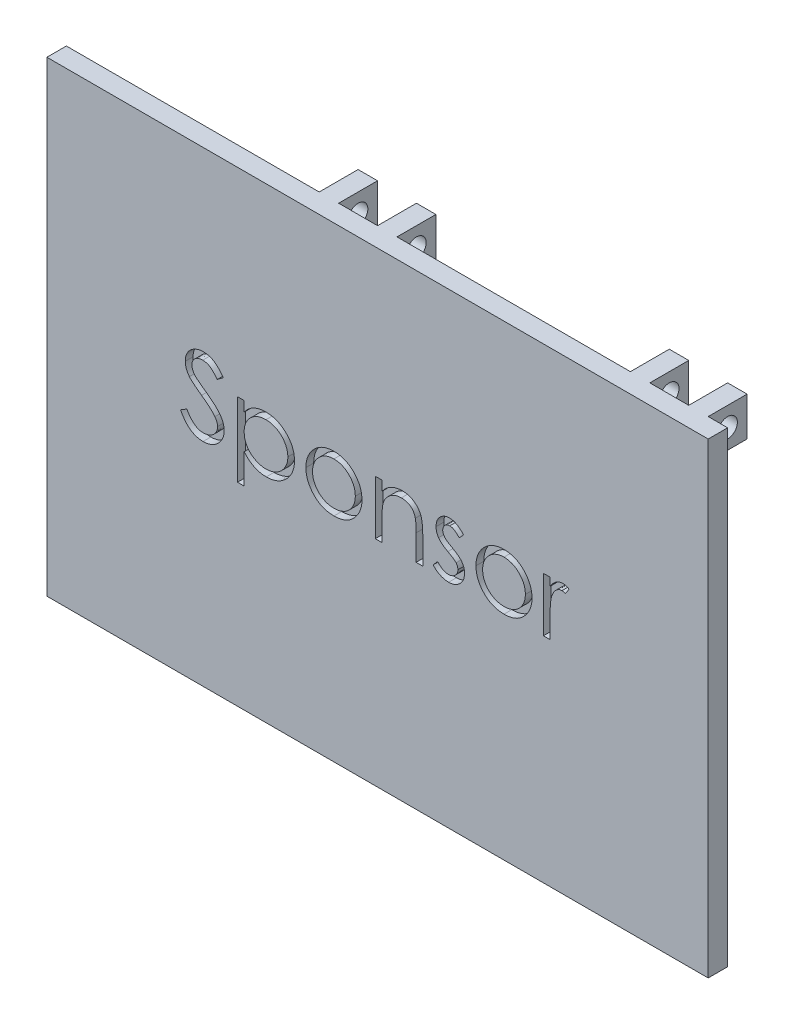
SolidWorks part; units mm, degrees
ref_plane "Plan de face" through (0, 0, 0) normal (0, 0, 1) x (1, 0, 0)
ref_plane "Plan de dessus" through (0, 0, 0) normal (0, 1, 0) x (1, 0, 0)
ref_plane "Plan de droite" through (0, 0, 0) normal (1, 0, 0) x (0, 0, -1)
sketch "Esquisse1" plane through (0, 0, 0) normal (0, 0, 1) x (1, 0, 0)
  line L1 (85, 60) -> (-85, 60)
  line L2 (85, 60) -> (85, -60)
  line L3 (85, -60) -> (-85, -60)
  line L4 (-85, 60) -> (-85, -60)
  line L5 (85, 60) -> (-85, -60) construction
  line L6 (85, -60) -> (-85, 60) construction
  point P0 (0, 0)
  dimension "D1" = 120
  dimension "D2" = 170
extrude "BASE" add sketch "Esquisse1" along normal blind 5
sketch "Esquisse2" plane through (0, 60, 0) normal (0, 1, 0) x (1, 0, 0)
  line L0 (85, 0) -> (-85, 0) construction
  line L1 (85, -5) -> (85, 0) construction
  line L2 (-15, 10) -> (-15, 0)
  line L3 (-15, 0) -> (-20, 0)
  line L4 (-5, 10) -> (-5, 0)
  line L5 (-5, 0) -> (0, 0)
  line L6 (-20, 0) -> (-20, 10)
  line L7 (-20, 10) -> (-15, 10)
  line L8 (0, 0) -> (0, 10)
  line L9 (0, 10) -> (-5, 10)
  line L10 (30, 15.4912) -> (30, -31.7182) construction
  line L11 (85, -5) -> (85, 0) construction
  line L12 (60, 10) -> (65, 10)
  line L13 (60, 0) -> (60, 10)
  line L14 (80, 10) -> (75, 10)
  line L15 (80, 0) -> (80, 10)
  line L16 (60, 0) -> (65, 0)
  line L17 (65, 10) -> (65, 0)
  line L18 (75, 0) -> (80, 0)
  line L19 (75, 10) -> (75, 0)
  line L20 (75, 0) -> (80, 0)
  point P0 (70, 0)
  point P1 (-10, 0)
  point P17 (85, -2.5)
  line M1 (85, 0) -> (-85, 0)
  dimension "D2" = 95
  dimension "D3" = 5
  dimension "D4" = 5
  dimension "D5" = 5
  dimension "D6" = 5
  dimension "D7" = 10
  dimension "D8" = 10
  dimension "D9" = 55
extrude "BOSS TIGE" add sketch "Esquisse2" against normal blind 10 contours L14 L19 L15 M1 | L17 L12 L13 M1 | L8 L9 L4 M1 | L7 L6 L2 M1
sketch "Esquisse4" plane through (0, 0, 5) normal (0, 0, 1) x (1, 0, 0)
  line L0 (-51.1463, -4.9958) -> (58.7709, -4.9958) construction
  text T0 "Sponsor" font "Century Gothic" height in points 72
extrude "VIDE SPONSOR" cut sketch "Esquisse4" against normal blind 2
sketch "Esquisse5" plane through (80, 0, 0) normal (1, 0, 0) x (0, 0, -1)
  line L0 (0, 60) -> (10, 50) construction
  line L1 (10, 50) -> (10, 55) construction
  line L2 (10, 50) -> (10, 60) construction
  line L3 (10, 55) -> (5, 55) construction
  circle A0 centre (5, 55) radius 2.5
  dimension "D1" = 5
extrude "Enlèv. mat.-Extru.3" cut sketch "Esquisse5" against normal through all
